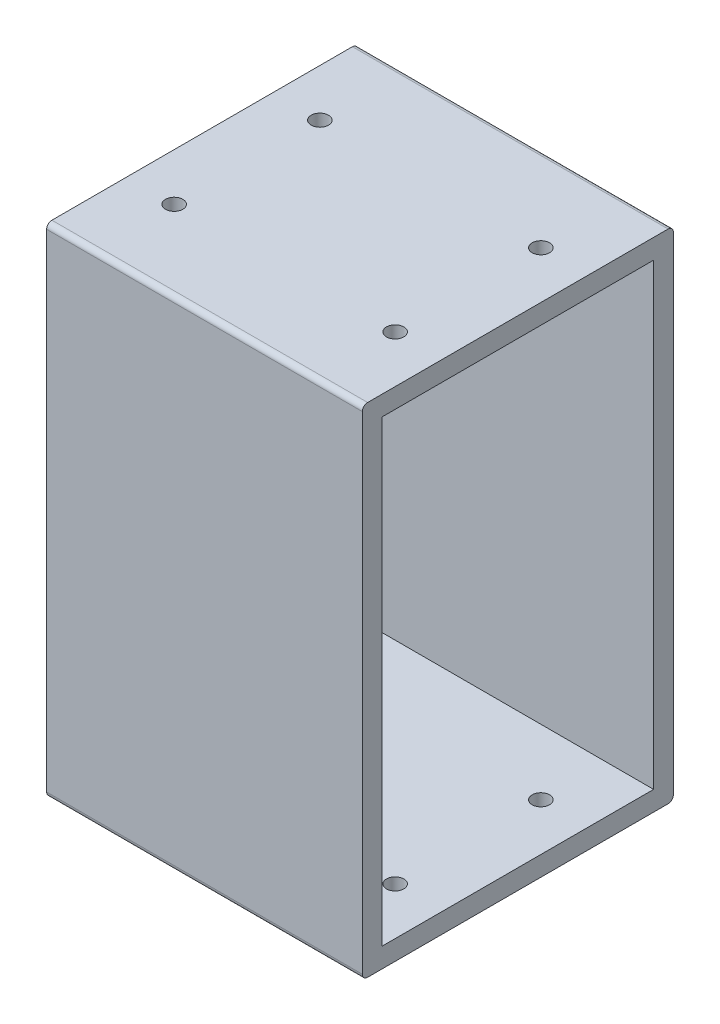
SolidWorks part; units mm, degrees
ref_plane "Front Plane" through (0, 0, 0) normal (0, 0, 1) x (1, 0, 0)
ref_plane "Top Plane" through (0, 0, 0) normal (0, 1, 0) x (1, 0, 0)
ref_plane "Right Plane" through (0, 0, 0) normal (1, 0, 0) x (0, 0, -1)
sketch "Sketch2" plane through (0, 0, 0) normal (1, 0, 0) x (0, 0, -1)
  line L1 (-37.5285, -60.071) -> (37.5285, -60.071)
  line L2 (-37.5285, -60.071) -> (-37.5285, 60.071)
  line L3 (-37.5285, 60.071) -> (37.5285, 60.071)
  line L4 (37.5285, -60.071) -> (37.5285, 60.071)
  line L5 (-37.5285, -60.071) -> (37.5285, 60.071) construction
  line L6 (-37.5285, 60.071) -> (37.5285, -60.071) construction
  point P0 (0, 0)
  dimension "D1" = 120.142
  dimension "D2" = 75.057
extrude "Boss-Extrude1" add sketch "Sketch2" along normal blind 76.2
sketch "Sketch3" plane through (0, 0, 37.5285) normal (0, 0, 1) x (1, 0, 0)
  line L12 (76.2, 60.071) -> (0, 60.071) construction
  line L13 (36.195, -60.071) -> (40.005, -60.071)
  line L14 (36.195, -60.071) -> (36.195, 60.071)
  line L15 (36.195, 60.071) -> (40.005, 60.071)
  line L16 (40.005, -60.071) -> (40.005, 60.071)
  line L17 (36.195, -60.071) -> (40.005, 60.071) construction
  line L18 (36.195, 60.071) -> (40.005, -60.071) construction
  point P0 (38.1, 0)
  point P7 (38.1, 60.071)
  point P8 (38.1, 60.071)
  dimension "D1" = 3.81
  dimension "D2" = 36.195
sketch "Sketch6" plane through (0, 0, 0) normal (-1, 0, 0) x (0, 0, 1)
  line L0 (-37.5285, 60.071) -> (37.5285, 60.071) construction
  line L1 (-32.766, -55.3085) -> (32.766, -55.3085)
  line L3 (-32.766, 55.3085) -> (32.766, 55.3085)
  line L4 (32.766, -55.3085) -> (32.766, 55.3085)
  line L5 (-32.766, 55.3085) -> (-32.766, -55.3085)
  line L7 (37.5285, 60.071) -> (37.5285, -60.071) construction
  line L8 (-37.5285, -60.071) -> (-37.5285, 60.071) construction
  point P0 (0, 0)
  point P10 (32.766, 0)
  dimension "D1" = 4.7625
  dimension "D2" = 4.7625
  dimension "D3" = 4.7625
extrude "Cut-Extrude1" cut sketch "Sketch6" against normal up to next
extrude "Boss-Extrude4" [suppressed] add sketch "Sketch3" along normal blind 5.08
sketch "Sketch8" [suppressed] plane through (0, 42.037, 0) normal (0, 1, 0) x (1, 0, 0)
  line L0 (76.2, 34.925) -> (0, 34.925) construction
  line L2 (36.195, -40.005) -> (36.195, 34.925)
  line L3 (36.195, 34.925) -> (40.005, 34.925)
  line L4 (40.005, -40.005) -> (40.005, 34.925)
  line L5 (36.195, -40.005) -> (40.005, -40.005)
extrude "Boss-Extrude5" [suppressed] add sketch "Sketch8" along normal blind 5.08
fillet "Fillet1" radius 1.27 4 edges at (38.1, -60.071, -37.5285) (38.1, 60.071, -37.5285) (38.1, -60.071, 37.5285) (38.1, 60.071, 37.5285)
sketch "Sketch7" plane through (0, -60.071, 0) normal (0, -1, 0) x (1, 0, 0)
  line L5 (0, 36.2585) -> (0, -36.2585) construction
  line L6 (76.2, 36.2585) -> (76.2, -36.2585) construction
  line L7 (76.2, -37.5285) -> (0, -37.5285) construction
  circle A0 centre (11.43, 18.1864) radius 2.0955
  circle A1 centre (64.77, 18.1864) radius 2.0955
  circle A2 centre (11.43, -16.9799) radius 2.0955
  circle A3 centre (64.77, -16.9799) radius 2.0955
  dimension "D3" = 4.191
  dimension "D1" = 19.3421
  dimension "D2" = 19.3421
  dimension "D4" = 11.43
  dimension "D5" = 11.43
  dimension "D6" = 20.5486
  dimension "D7" = 20.5486
  dimension "D8" = 11.43
  dimension "D9" = 11.43
extrude "Cut-Extrude3" cut sketch "Sketch7" against normal through all both and the other way through all
